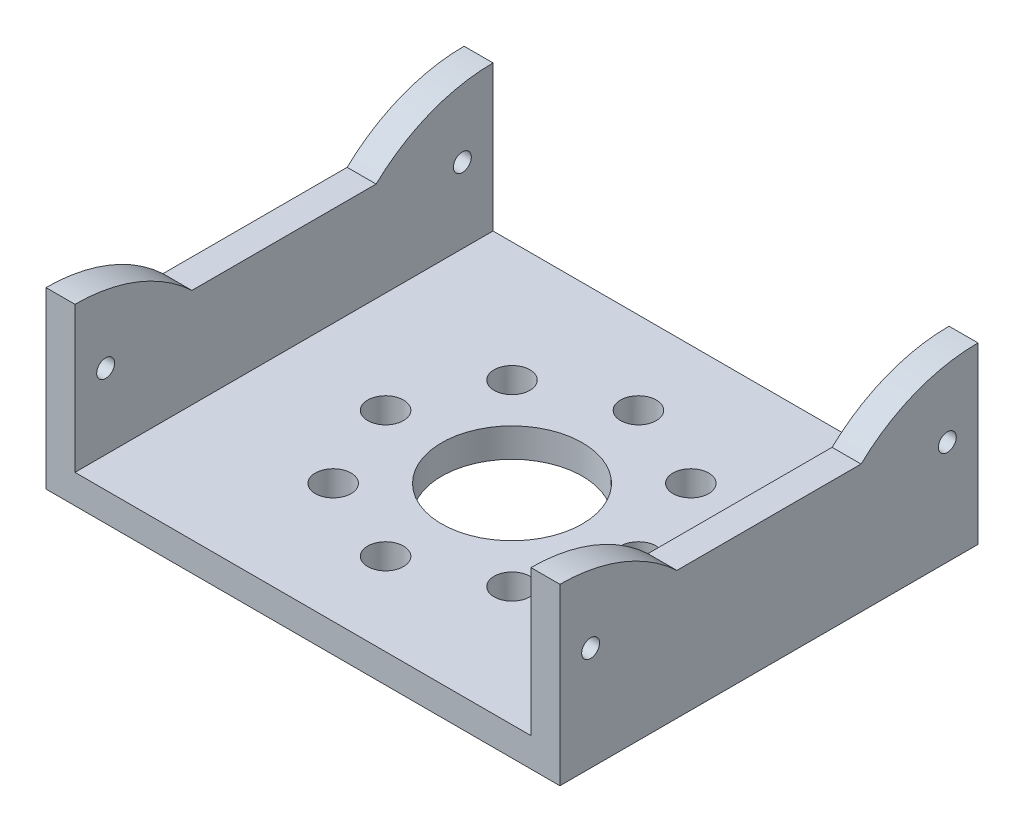
SolidWorks part; units mm, degrees
ref_plane "Front Plane" through (0, 0, 0) normal (0, 0, 1) x (1, 0, 0)
ref_plane "Top Plane" through (0, 0, 0) normal (0, 1, 0) x (1, 0, 0)
ref_plane "Right Plane" through (0, 0, 0) normal (1, 0, 0) x (0, 0, -1)
sketch "Sketch1" plane through (0, 0, 0) normal (0, 0, 1) x (1, 0, 0)
  line L0 (0, 0) -> (-14.37, 0)
  line L1 (-14.37, 0) -> (-14.37, 9.76)
  line L2 (-14.37, 9.76) -> (-12.75, 9.76)
  line L3 (-12.75, 9.76) -> (-12.75, 1.62)
  line L4 (-12.75, 1.62) -> (0, 1.62)
  line L5 (0, 1.62) -> (0, 0)
  point P7 (-13.56, 9.76)
  point P8 (-6.375, 1.62)
  dimension "D1" = 14.37
  dimension "D2" = 9.76
  dimension "D3" = 1.62
  dimension "D4" = 1.62
extrude "Boss-Extrude1" add sketch "Sketch1" along normal blind 23.38
sketch "Sketch2" plane through (-14.37, 0, 0) normal (-1, 0, 0) x (0, 0, 1)
  line L0 (0, 9.76) -> (0, 0) construction
  line L1 (6.5399, 7.1636) -> (16.8401, 7.1636)
  line L2 (1.715, 5.81) -> (21.665, 5.81) construction
  line L3 (23.38, 9.76) -> (23.38, 0) construction
  line L4 (11.69, 5.81) -> (11.69, 7.1636) construction
  line L5 (23.38, 0.2254) -> (23.38, 9.76) construction
  line L6 (0, 9.76) -> (0, 14.7448)
  line L7 (0, 14.7448) -> (23.38, 14.7448)
  line L8 (23.38, 14.7448) -> (23.38, 9.76)
  line L9 (11.69, 0) -> (11.69, 5.81) construction
  line L10 (23.38, 9.76) -> (0, 9.76) construction
  line L11 (23.38, 0) -> (0, 0) construction
  arc A0 (0, 9.76) -> (6.5399, 7.1636) centre (0, 0.2254) cw
  arc A1 (16.8401, 7.1636) -> (23.38, 9.76) centre (23.38, 0.2254) cw
  circle A2 centre (1.715, 5.81) radius 0.5
  circle A3 centre (21.665, 5.81) radius 0.5
  point P15 (11.69, 5.81)
  point P19 (11.69, 9.76)
  point P23 (1.715, 5.81)
  dimension "D2" = 1
  dimension "D4" = 1
  dimension "D1" = 5.81
  dimension "D3" = 9.975
extrude "Cut-Extrude1" cut sketch "Sketch2" against normal blind 44.5
mirror "Mirror1" about plane through (0, 1.62, 23.38) normal (-1, 0, 0) of "Cut-Extrude1", "Boss-Extrude1"
sketch "Sketch3" plane through (0, 0, 0) normal (0, 1, 0) x (1, 0, 0)
  line L2 (12.75, -23.38) -> (12.75, 0) construction
  line L3 (5, -6.69) -> (-5, -6.69) construction
  line L4 (5, -6.69) -> (5, 3.31) construction
  line L6 (-5, -6.69) -> (-5, 3.31) construction
  line L7 (5, -6.69) -> (-5, 3.31) construction
  line L8 (5, 3.31) -> (-5, -6.69) construction
  circle A0 centre (0, -11.69) radius 7.0711 construction
  circle A1 centre (-7.0711, -11.69) radius 1
  circle A2 centre (7.0711, -11.69) radius 1
  circle A3 centre (5, -6.69) radius 1
  circle A4 centre (-5, -6.69) radius 1
  circle A5 centre (0, -11.69) radius 3.935
  circle A6 centre (-5, -16.69) radius 1
  circle A7 centre (5, -16.69) radius 1
  circle A8 centre (0, -18.7611) radius 1
  circle A9 centre (0, -4.6189) radius 1
  circle A11 centre (-5, -26.69) radius 1 [skipped]
  circle A12 centre (5, -26.69) radius 1 [skipped]
  point P13 (12.75, -11.69)
  dimension "D5" = 10
  dimension "D6" = 3
extrude "Cut-Extrude2" cut sketch "Sketch3" along normal blind 20.5
